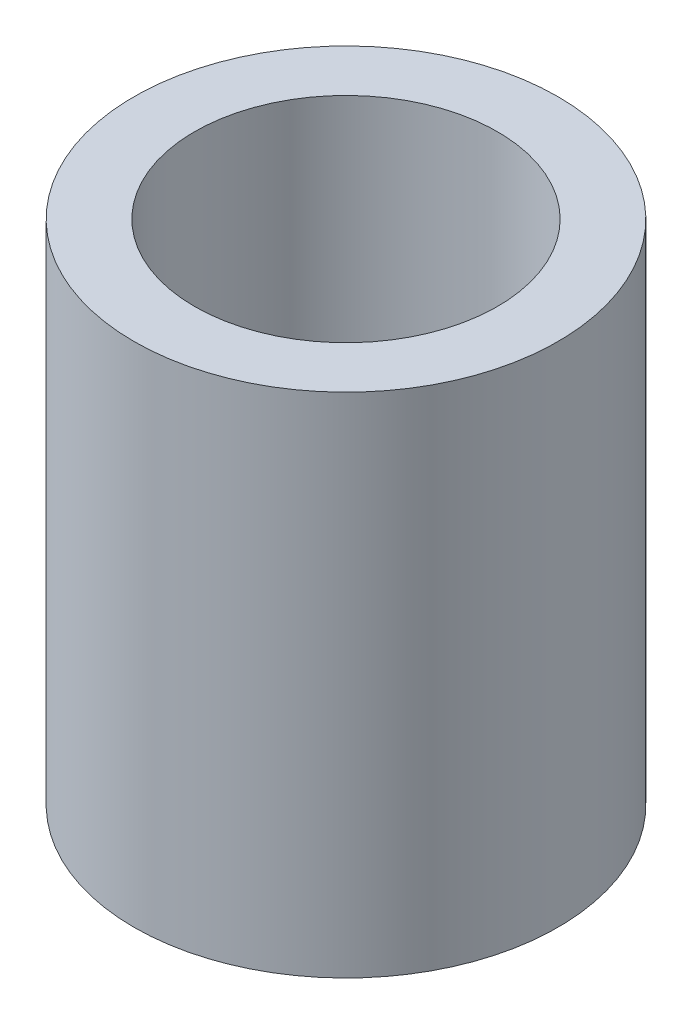
SolidWorks part; units mm, degrees
ref_plane "Alzado" through (0, 0, 0) normal (0, 0, 1) x (1, 0, 0)
ref_plane "Planta" through (0, 0, 0) normal (0, 1, 0) x (1, 0, 0)
ref_plane "Vista lateral" through (0, 0, 0) normal (1, 0, 0) x (0, 0, -1)
sketch "Croquis1" plane through (0, 0, 0) normal (0, 1, 0) x (1, 0, 0)
  circle A0 centre (0, 0) radius 10
  circle A1 centre (0, 0) radius 14
  dimension "D1" = 28
  dimension "D2" = 20
extrude "Saliente-Extruir1" add sketch "Croquis1" along normal mid plane 33.5
